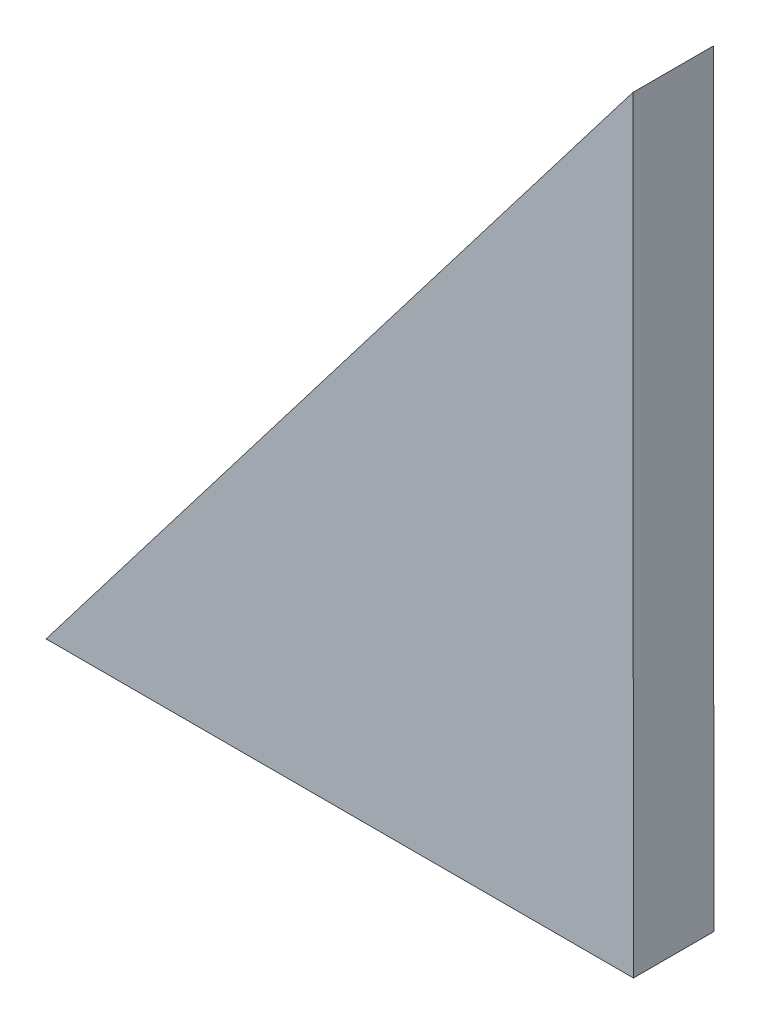
SolidWorks part; units mm, degrees
ref_plane "Front Plane" through (0, 0, 0) normal (0, 0, 1) x (1, 0, 0)
ref_plane "Top Plane" through (0, 0, 0) normal (0, 1, 0) x (1, 0, 0)
ref_plane "Right Plane" through (0, 0, 0) normal (1, 0, 0) x (0, 0, -1)
sketch "Sketch1" plane through (0, 0, 0) normal (0, 0, 1) x (1, 0, 0)
  line L0 (-1000, 0) -> (49000, 0) construction
  line L1 (-92.7285, 0) -> (30296.857, 39704.8245) construction
  line L2 (-0.1011, -961.0603) -> (-0.1011, 49038.9397) construction
  line L3 (-92.7285, 0) -> (-95.0822, 1.8015) construction
  line L4 (-0.1011, 121.0203) -> (-10.7678, 129.1845) construction
  line L5 (-0.1011, 121.0203) -> (0, 0)
  line L6 (0, 0) -> (-92.7285, 0)
  line L7 (-92.7285, 0) -> (-0.1011, 121.0203)
  dimension "D1" = 52.57
  dimension "D2" = 152.4
extrude "Extrude1" add sketch "Sketch1" along normal blind 12.7
